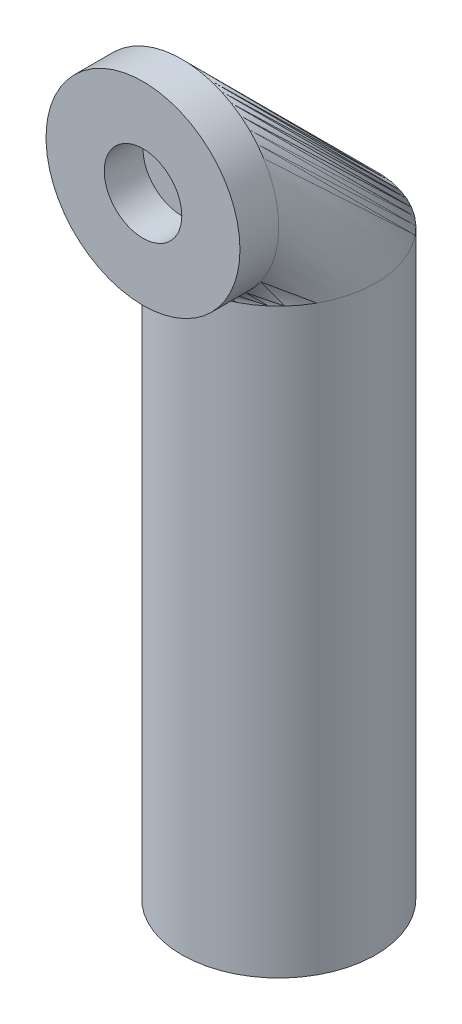
SolidWorks part; units mm, degrees
other "Markup1"
sketch "Sketch7" plane through (50, -100, 90) normal (0.8604, -0.4148, 0.2959) x (-0.1073, 0.4202, 0.9011)
other "Markup2"
sketch "Sketch8" plane through (50, -100, 90) normal (0.8604, -0.4148, 0.2959) x (-0.1073, 0.4202, 0.9011)
ref_plane "Front Plane" through (0, 0, 0) normal (0, 0, 1) x (1, 0, 0)
ref_plane "Top Plane" through (0, 0, 0) normal (0, 1, 0) x (1, 0, 0)
ref_plane "Right Plane" through (0, 0, 0) normal (1, 0, 0) x (0, 0, -1)
sketch "Sketch1" plane through (0, 0, 0) normal (0, 1, 0) x (1, 0, 0)
  circle A0 centre (0, 0) radius 50
extrude "Boss-Extrude1" add sketch "Sketch1" along normal blind 300
sketch "Sketch2" plane through (0, 0, 0) normal (1, 0, 0) x (0, 0, -1)
  arc A2 (0, 300) -> (-50, 350) centre (-50, 300) ccw
sketch "Sketch3" plane through (0, 300, 0) normal (0, 1, 0) x (1, 0, 0)
  circle A0 centre (0, 0) radius 50
sweep "Sweep1" add profiles "Sketch3" path "Sketch2"
ref_plane "Plane2" through (0, 150, 0) normal (0, 1, 0) x (1, 0, 0)
sketch "Sketch4" plane through (0, 0, 50) normal (0, 0, 1) x (1, 0, 0)
  line L0 (0, 300) -> (0, 350) construction
  circle A0 centre (0, 350) radius 50
extrude "Boss-Extrude2" add sketch "Sketch4" along normal blind 20
sketch "Sketch5" plane through (0, 0, 70) normal (0, 0, 1) x (1, 0, 0)
  circle A0 centre (0, 350) radius 20
extrude "Cut-Extrude1" cut sketch "Sketch5" against normal blind 20
sketch "Sketch9" plane through (0, 0, 0) normal (0, -1, 0) x (1, 0, 0)
  circle A0 centre (0, 0) radius 20
extrude "Cut-Extrude2" cut sketch "Sketch9" against normal blind 20
